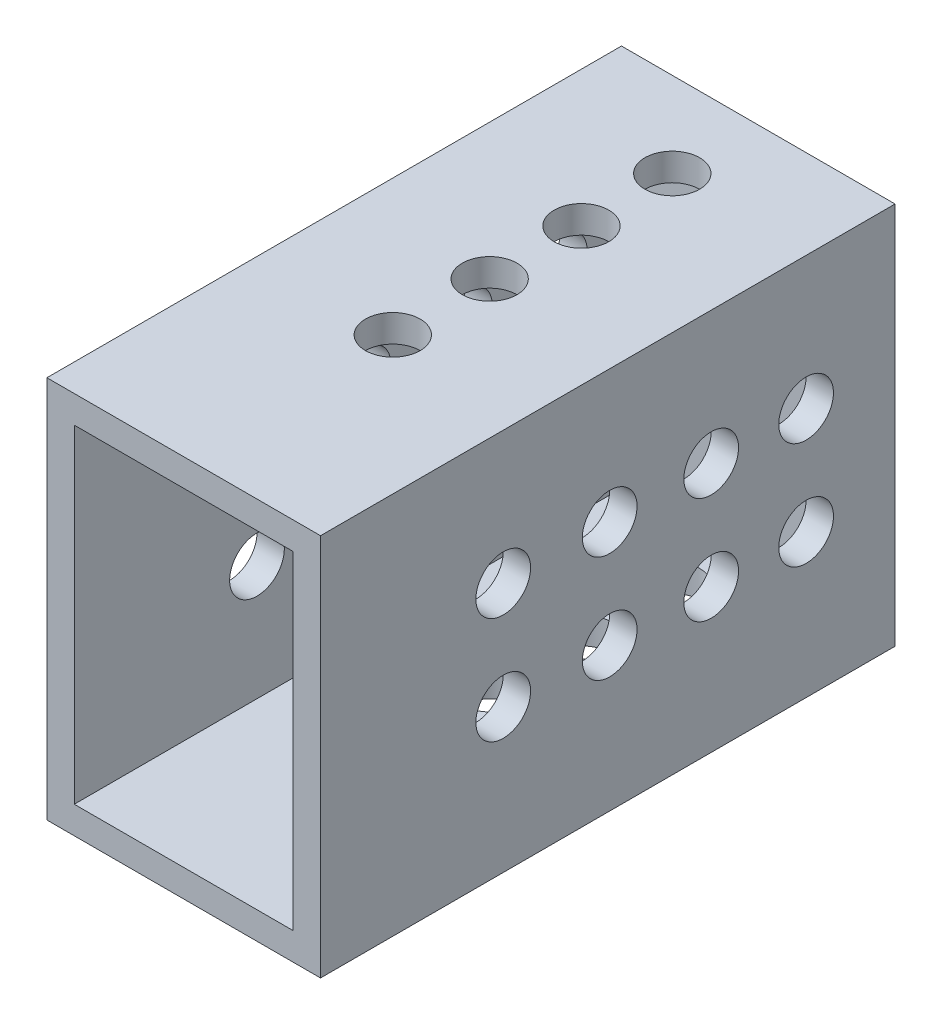
SolidWorks part; units mm, degrees
ref_plane "Plan de face" through (0, 0, 0) normal (0, 0, 1) x (1, 0, 0)
ref_plane "Plan de dessus" through (0, 0, 0) normal (0, 1, 0) x (1, 0, 0)
ref_plane "Plan de droite" through (0, 0, 0) normal (1, 0, 0) x (0, 0, -1)
sketch "Esquisse1" plane through (0, 0, 0) normal (0, 0, 1) x (1, 0, 0)
  line L1 (-46.2206, -22.1959) -> (-36.2206, -22.1959)
  line L2 (-46.2206, -22.1959) -> (-46.2206, -36.1959)
  line L3 (-46.2206, -36.1959) -> (-36.2206, -36.1959)
  line L4 (-36.2206, -22.1959) -> (-36.2206, -36.1959)
  dimension "D1" = 14
  dimension "D2" = 10
extrude "Boss.-Extru.1" add sketch "Esquisse1" along normal blind 1
sketch "Esquisse2" plane through (0, 0, 1) normal (0, 0, 1) x (1, 0, 0)
  line L1 (-46.2206, -22.1959) -> (-36.2206, -22.1959)
  line L2 (-46.2206, -22.1959) -> (-46.2206, -36.1959)
  line L3 (-46.2206, -36.1959) -> (-36.2206, -36.1959)
  line L4 (-36.2206, -22.1959) -> (-36.2206, -36.1959)
  line L5 (-45.2206, -23.1959) -> (-37.2206, -23.1959)
  line L6 (-45.2206, -23.1959) -> (-45.2206, -35.1959)
  line L7 (-45.2206, -35.1959) -> (-37.2206, -35.1959)
  line L8 (-37.2206, -23.1959) -> (-37.2206, -35.1959)
  dimension "D1" = 1
  dimension "D2" = 1
  dimension "D3" = 1
  dimension "D4" = 1
extrude "Boss.-Extru.2" add sketch "Esquisse2" along normal blind 20
sketch "Esquisse3" plane through (-46.2206, 0, 0) normal (-1, 0, 0) x (0, 0, 1)
  circle A0 centre (3.2521, -27.0447) radius 1
  circle A1 centre (10.4309, -27.0447) radius 1
  circle A2 centre (6.7209, -30.9483) radius 1
  circle A3 centre (10.4309, -30.9483) radius 1
  circle A4 centre (14.3219, -30.9483) radius 1
  circle A5 centre (14.3219, -27.0447) radius 1
  circle A6 centre (6.7209, -27.0447) radius 1
  circle A7 centre (3.2521, -30.9483) radius 1
  dimension "D1" = 2
extrude "Enlèv. mat.-Extru.1" cut sketch "Esquisse3" against normal through all
sketch "Esquisse4" plane through (0, -22.1959, 0) normal (0, 1, 0) x (1, 0, 0)
  circle A0 centre (-41.2574, -3.1068) radius 1
  circle A1 centre (-41.2574, -6.4254) radius 1
  circle A2 centre (-41.2574, -9.781) radius 1
  circle A3 centre (-41.2574, -13.3209) radius 1
  dimension "D1" = 2
extrude "Enlèv. mat.-Extru.2" cut sketch "Esquisse4" against normal through all
